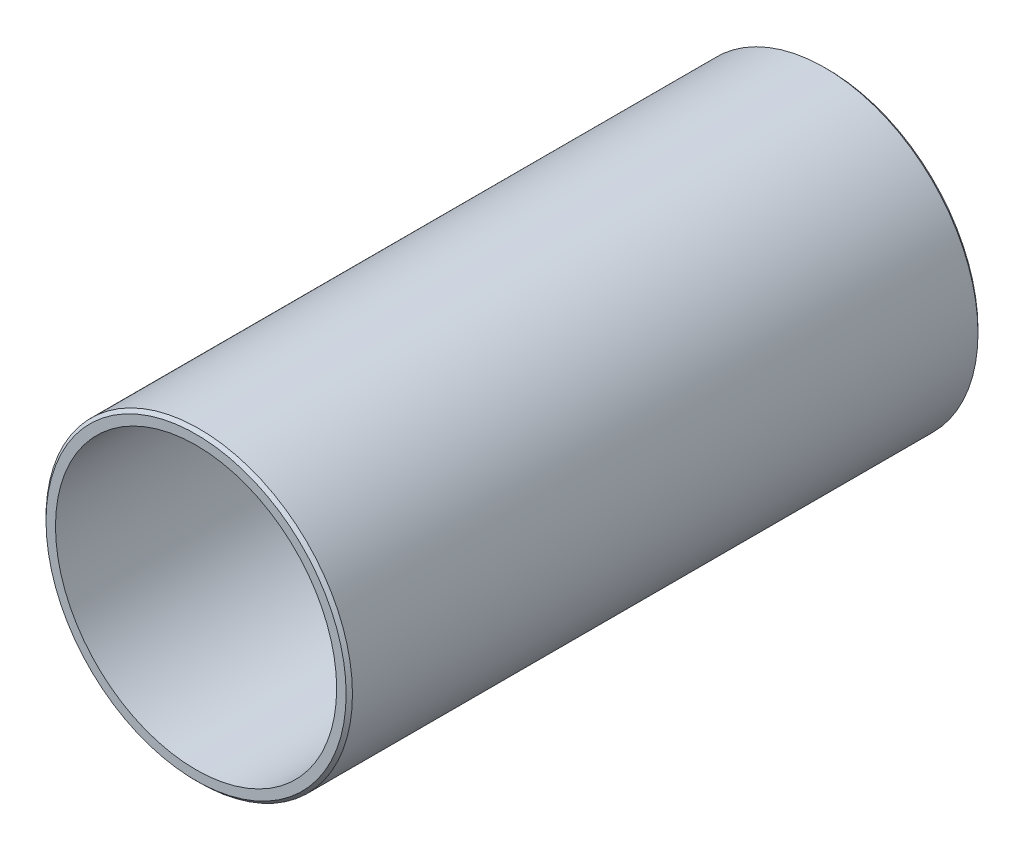
SolidWorks part; units mm, degrees
material "20"
ref_plane "前视基准面" through (0, 0, 0) normal (0, 0, 1) x (1, 0, 0)
ref_plane "上视基准面" through (0, 0, 0) normal (0, 1, 0) x (1, 0, 0)
ref_plane "右视基准面" through (0, 0, 0) normal (1, 0, 0) x (0, 0, -1)
sketch "草图2" plane through (0, 0, 0) normal (0, 0, 1) x (1, 0, 0)
  circle A0 centre (0, 0) radius 89
  circle A1 centre (0, 0) radius 97
  dimension "D1" = 178
  dimension "D2" = 194
extrude "凸台-拉伸1" add sketch "草图2" along normal mid plane 400
chamfer "倒角1" distance 2 angle 45 2 edges at (97, 0, 200) (97, 0, -200)
